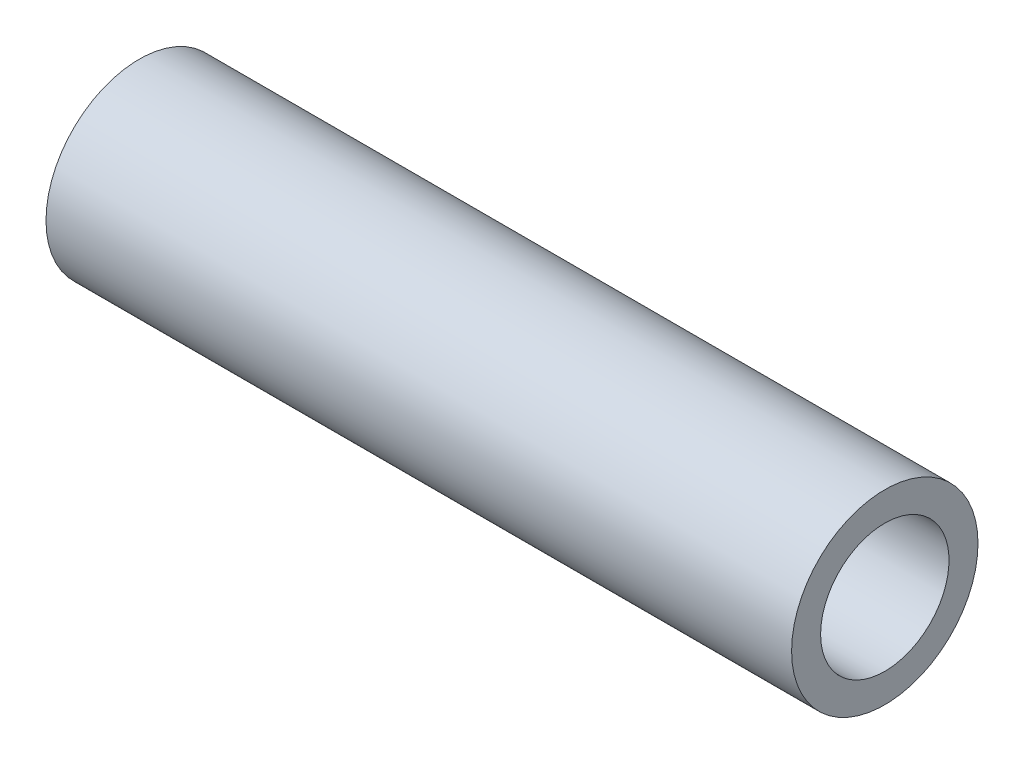
SolidWorks part; units mm, degrees
ref_plane "Front Plane" through (0, 0, 0) normal (0, 0, 1) x (1, 0, 0)
ref_plane "Top Plane" through (0, 0, 0) normal (0, 1, 0) x (1, 0, 0)
ref_plane "Right Plane" through (0, 0, 0) normal (1, 0, 0) x (0, 0, -1)
sketch "Sketch1" plane through (0, 0, 0) normal (0, 0, 1) x (1, 0, 0)
  line L0 (0, 0) -> (10342.9254, 0) construction
  line L2 (0, 2.25) -> (18, 2.25)
  line L3 (0, 2.25) -> (0, 1.55)
  line L4 (0, 1.55) -> (18, 1.55)
  line L5 (18, 2.25) -> (18, 1.55)
  dimension "D1" = 18
  dimension "D2" = 3.1
  dimension "D3" = 4.5
revolve "Revolve1" add sketch "Sketch1" angle 360 about L0
